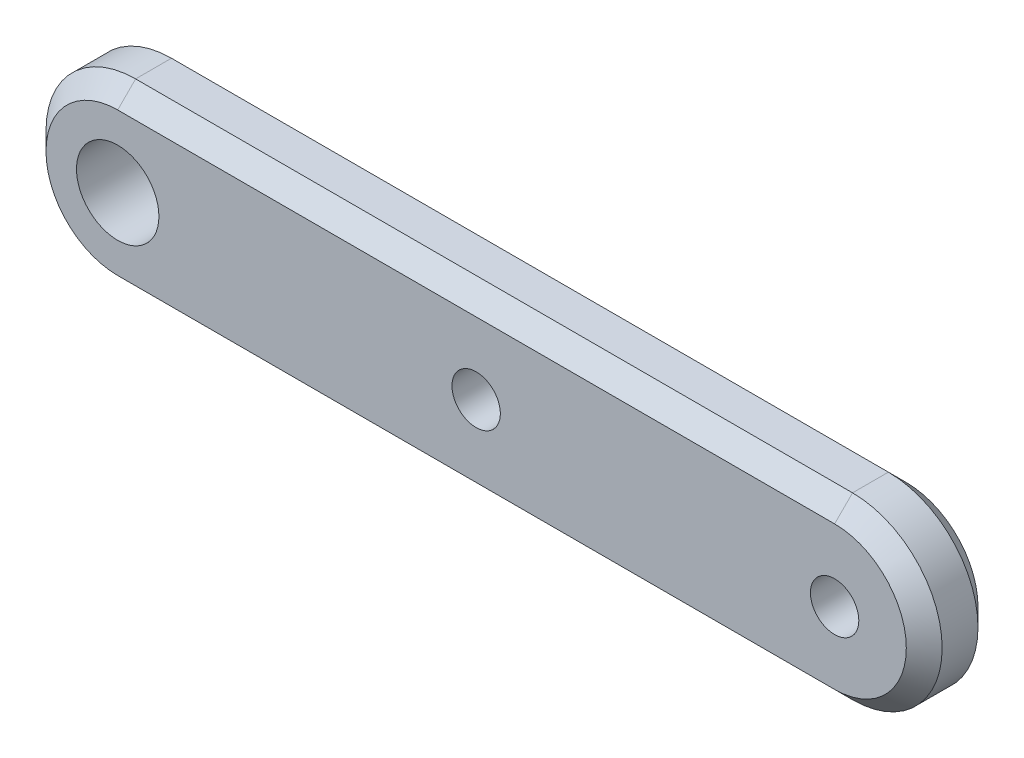
SolidWorks part; units mm, degrees
material "Delrin 2700 NC010, Low Viscosity Acetal Copolymer (SS)"
ref_plane "Front Plane" through (0, 0, 0) normal (0, 0, 1) x (1, 0, 0)
ref_plane "Top Plane" through (0, 0, 0) normal (0, 1, 0) x (1, 0, 0)
ref_plane "Right Plane" through (0, 0, 0) normal (1, 0, 0) x (0, 0, -1)
sketch "Sketch1" plane through (0, 0, 0) normal (0, 0, 1) x (1, 0, 0)
  line L0 (0, 5) -> (40, 5)
  line L1 (40, -5) -> (0, -5)
  line L2 (0, 0) -> (40, 0) construction
  circle A0 centre (0, 0) radius 5
  circle A1 centre (40, 0) radius 5
  circle A2 centre (40, 0) radius 1.35
  circle A3 centre (0, 0) radius 2.3
  circle A4 centre (20, 0) radius 1.35
  dimension "D1" = 10
  dimension "D2" = 40
  dimension "D3" = 2.7
  dimension "D4" = 4.6
extrude "Boss-Extrude1" add sketch "Sketch1" along normal blind 4 contours A1 L0 A0 L1 | A1 A2 | A0 A3 | L2 A0 L1 A1 A4
chamfer "Chamfer1" distance 1 angle 45 8 edges at (20, -5, 0) (-5, 0, 0) (45, 0, 0) (20, 5, 0) (20, -5, 4) (-5, 0, 4) (45, 0, 4) (20, 5, 4)
ref_plane "Plane1" through (0, 0, 2) normal (0, 0, 1) x (1, 0, 0)
